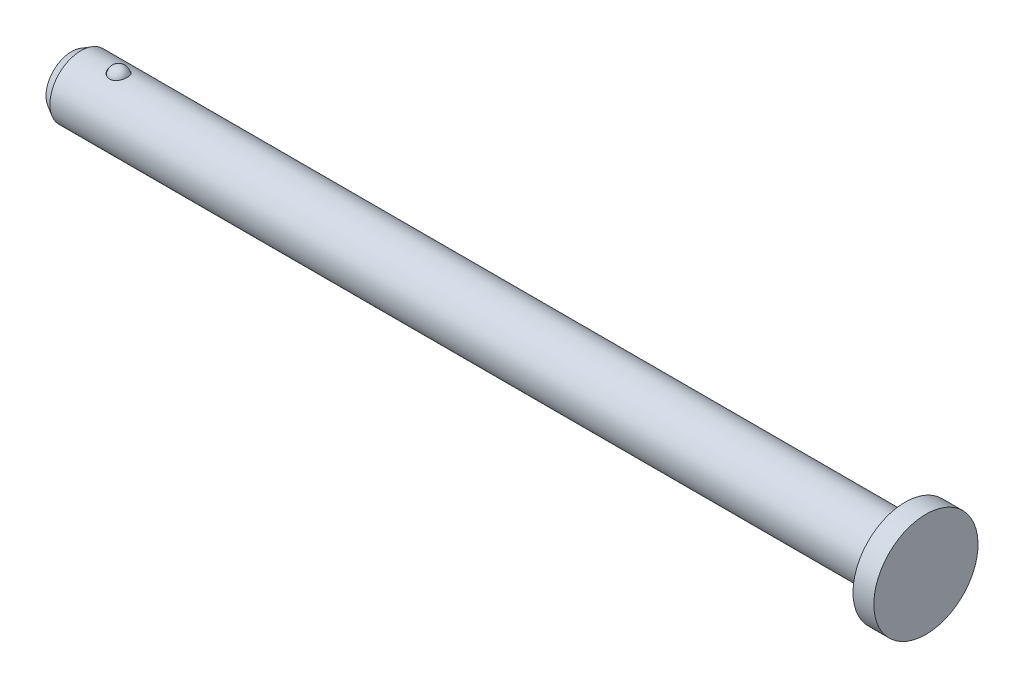
SolidWorks part; units mm, degrees
other "Imported1"
other "Imported2" parameters "D1"=138.0715, "Length"=138.0715, "Usable Length"=107.0085, "Head Height"=13.3603, "Head Diameter"=7.9375, "Diameter"=4.7244, "Shaft Length"=63.5, "Ball Height"=5.1816, "Ball Width"=2.3622, "D2"=54.5332, "F"=55.499, "D10"=11.2649, "D11"=5.3256, "D4"=6.8632, "K"=3.175, "A"=19.0119, "B"=7.112, "D"=21.59, "E"=9.525, "D3"=24.257, "H"=41.275, "D5"=24.257, "Useable Length"=25.4, "D6"=0.9873, "D7"=3.8918, "D8"=4.5254, "D9"=5.5856, "G"=64.77, "D12"=34.036, "C"=6.8932, "A1"=15, "D13"=1.6682, "J"=3.048, "D14"=90, "D15"=34.5361, "Head Dia"=9.525
ref_plane "Front" through (0, 0, 0) normal (0, 0, 1) x (1, 0, 0)
ref_plane "Top" through (0, 0, 0) normal (0, 1, 0) x (1, 0, 0)
ref_plane "Right" through (0, 0, 0) normal (1, 0, 0) x (0, 0, -1)
sketch "Sketch4" plane through (0, 0, 0) normal (0, 0, 1) x (1, 0, 0)
  line L0 (-28.9624, -2.3622) -> (-28.9623, 2.8194) construction
  line L1 (32.5437, -2.3622) -> (-32.5438, -2.3622) construction
  line L2 (32.5437, -2.3622) -> (32.5437, 2.3622) construction
  line L3 (32.5437, 2.3622) -> (-32.5438, 2.3622) construction
  line L4 (-32.5438, -2.3622) -> (-32.5438, 2.3622) construction
  line L5 (32.5437, -2.3622) -> (-32.5438, 2.3622) construction
  line L6 (32.5437, 2.3622) -> (-32.5438, -2.3622) construction
  line L7 (32.5437, 3.9688) -> (30.9562, 3.9687)
  line L8 (32.5437, 3.9688) -> (32.5437, -3.9688)
  line L9 (32.5437, -3.9688) -> (30.9562, -3.9688)
  line L10 (30.9562, 3.9687) -> (30.9562, -3.9688)
  line L11 (32.5437, 3.9688) -> (30.9562, -3.9688) construction
  line L12 (32.5437, -3.9688) -> (30.9562, 3.9687) construction
  line L13 (-27.7812, 2.3622) -> (-30.1435, 2.3622) construction
  point P0 (0, 0)
  point P6 (-27.7812, 2.3622)
  point P12 (31.75, 0)
  point P17 (-28.9624, 2.3622)
  dimension "Head Height" = 1.5875
sketch "Sketch1" plane through (0, 0, 0) normal (0, 0, 1) x (1, 0, 0)
  line L0 (32.5437, 3.9688) -> (30.9562, 3.9688)
  line L1 (30.9562, 2.3622) -> (30.9562, 3.9688)
  line L4 (32.5437, 3.9688) -> (32.5437, 0)
  line L5 (32.5437, 3.9688) -> (32.5437, -3.9688) construction
  line L6 (30.9562, 3.9687) -> (30.9562, -3.9688) construction
  line L9 (32.5437, 3.9688) -> (30.9562, 3.9688) construction
  line L13 (-32.5438, -2.3622) -> (-32.5438, 2.3622) construction
  line L16 (30.9562, 2.3622) -> (-31.8351, 2.3622)
  line L17 (-32.5437, 2.3622) -> (-32.5438, 1.9531) construction
  line L19 (-31.8351, 2.3622) -> (-32.5437, 2.3622) construction
  line L22 (-32.5438, -2.3622) -> (-31.8351, -2.3622) construction
  line L24 (-32.5438, 0) -> (32.5437, 0)
  line L26 (-28.9624, -2.3622) -> (-28.9624, 2.8194) construction
  line L27 (32.5437, -2.3622) -> (-32.5438, 2.3622) construction
  line L29 (-32.5438, 0) -> (-32.5438, -1.9531) construction
  line L36 (30.9562, 0) -> (30.9562, 2.3622) construction
  line L37 (-32.5438, 1.9531) -> (-32.5438, 0)
  line L38 (-31.8351, -2.3622) -> (32.5437, -2.3622) construction
  line L39 (-32.5438, -1.9531) -> (-32.5438, -2.3622) construction
  line L40 (-31.8351, 2.3622) -> (-32.5438, 1.9531)
  line L42 (-31.8351, -2.3622) -> (-32.5438, -1.9531) construction
  line L43 (-31.8351, 2.3622) -> (-31.8351, -2.3622) construction
  circle A0 centre (-28.9624, 2.1508) radius 0.6686 construction
  point P4 (32.5437, 1.9844)
  point P26 (-29.631, 2.1508)
  point P35 (-28.9624, 2.3622)
  dimension "D1" = 30
  dimension "D2" = 0.7087
revolve "Revolve1" add sketch "Sketch1" angle 360 about L24
sketch "Sketch2" plane through (0, 0, 0) normal (0, 0, 1) x (1, 0, 0)
  line L0 (-28.2683, 2.1508) -> (-29.6564, 2.1508)
  line L1 (-28.9624, 2.8194) -> (-28.9624, 2.8448) construction
  line L2 (-28.2683, 2.1508) -> (-26.8803, 2.1508) construction
  circle A1 centre (-28.9624, 2.1508) radius 0.6686 construction
  arc A2 (-29.6564, 2.1508) -> (-28.2683, 2.1508) centre (-28.9624, 2.1508) cw
  circle A4 centre (-28.9624, 2.1508) radius 0.6686 construction
  dimension "D1" = 0.0254
revolve "Cut-Revolve1" cut sketch "Sketch2" angle 360 about L2
sketch "Sketch3" plane through (0, 0, 0) normal (0, 0, 1) x (1, 0, 0)
  line L0 (-28.2937, 2.1508) -> (-29.631, 2.1508)
  line L1 (-28.2937, 2.1508) -> (-26.9565, 2.1508) construction
  arc A1 (-28.2937, 2.1508) -> (-29.631, 2.1508) centre (-28.9624, 2.1508) ccw
  circle A2 centre (-28.9624, 2.1508) radius 0.6686 construction
  point P5 (-28.2937, 2.1508)
revolve "Revolve2" add sketch "Sketch3" angle 360 about L1
equation "\"Ball Width@Sketch4\"=\"Diameter@Sketch4\"*.5"
equation "\"D2@Sketch1\"= \"Diameter@Sketch4\" * .15"
